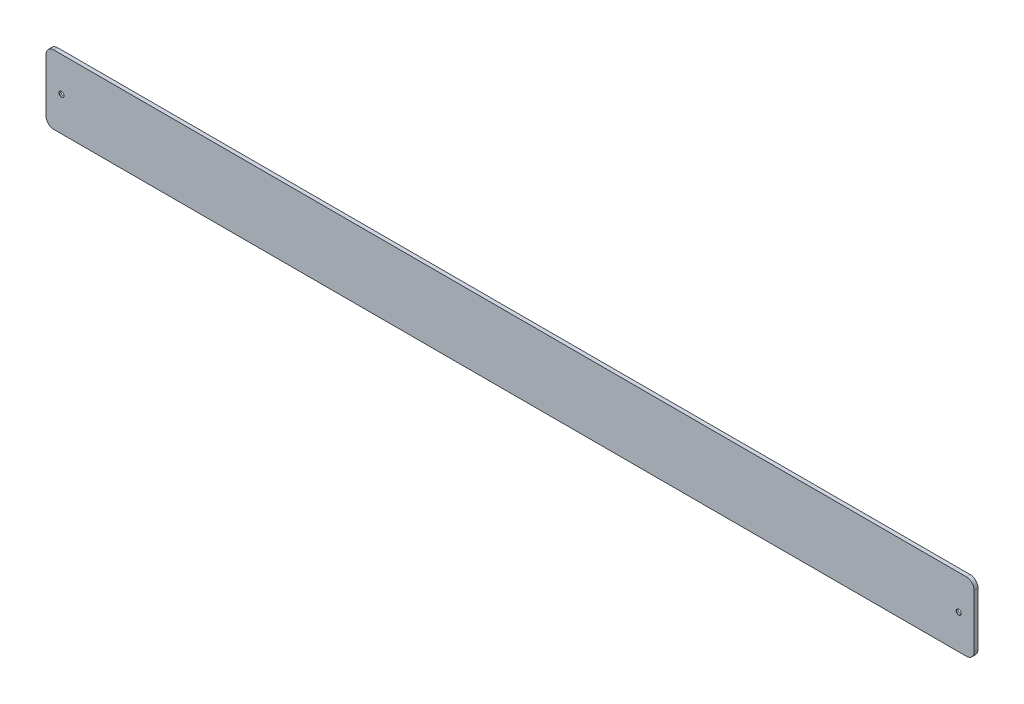
SolidWorks part; units mm, degrees
ref_plane "Plan de face" through (0, 0, 0) normal (0, 0, 1) x (1, 0, 0)
ref_plane "Plan de dessus" through (0, 0, 0) normal (0, 1, 0) x (1, 0, 0)
ref_plane "Plan de droite" through (0, 0, 0) normal (1, 0, 0) x (0, 0, -1)
sketch "Esquisse1" plane through (0, 0, 0) normal (0, 0, 1) x (1, 0, 0)
  line L1 (-1067.2805, -44.5) -> (112.7195, -44.5)
  line L2 (-1077.2805, -34.5) -> (-1077.2805, 34.5)
  line L3 (-1067.2805, 44.5) -> (112.7195, 44.5)
  line L4 (122.7195, -34.5) -> (122.7195, 34.5)
  line L5 (-1077.2805, -44.5) -> (122.7195, 44.5) construction
  line L6 (-1077.2805, 44.5) -> (122.7195, -44.5) construction
  arc A0 (-1067.2805, -44.5) -> (-1077.2805, -34.5) centre (-1067.2805, -34.5) cw
  arc A1 (-1077.2805, 34.5) -> (-1067.2805, 44.5) centre (-1067.2805, 34.5) cw
  arc A2 (112.7195, -44.5) -> (122.7195, -34.5) centre (112.7195, -34.5) ccw
  arc A3 (122.7195, 34.5) -> (112.7195, 44.5) centre (112.7195, 34.5) ccw
  point P0 (-477.2805, 0)
  dimension "D3" = 10
  dimension "D1" = 89
  dimension "D2" = 1200
extrude "Boss.-Extru.1" add sketch "Esquisse1" along normal blind 5
hole_wizard "Dégagement M61" positions "Esquisse3" profile "Esquisse2" hole size "M6" standard "JIS" end condition through all
sketch "Esquisse3" plane through (0, 0, 5) normal (0, 0, 1) x (1, 0, 0)
  point P0 (-1057.2805, -0.1767)
  point P2 (102.7195, 0)
sketch "Esquisse2" plane through (-1057.2805, -0.1767, 5) normal (1, 0, 0) x (0, -1, 0)
  line L0 (0, 0) -> (0, 5)
  line L1 (0, 5) -> (3.3, 5)
  line L2 (3.3, 5) -> (3.3, 0)
  line L5 (3.3, 0) -> (0, 0)
  line L11 (0, -6.35) -> (0, 107.95) construction
  dimension "Diamètre du perçage jusqu'au prochain" = 6.6
  dimension "Profondeur du perçage jusqu'au prochain" = 5
hole_wizard "Chambrage pour vis à tête ronde bombée M61" positions "Esquisse5" profile "Esquisse4" counterbore size "M6" standard "Ansi Metric" end condition through all
sketch "Esquisse5" plane through (0, 0, 0) normal (0, 0, -1) x (-1, 0, 0)
  point P0 (-102.7195, 0)
  point P2 (1057.2805, -0.1767)
sketch "Esquisse4" plane through (102.7195, 0, 0) normal (1, 0, 0) x (0, 1, 0)
  line L0 (0, 0) -> (0, 5)
  line L1 (0, 5) -> (3.3, 5)
  line L2 (3.3, 4.625) -> (3.3, 5)
  line L3 (3.3, 4.625) -> (3.325, 4.6)
  line L4 (3.325, 4.6) -> (6.5, 4.6)
  line L5 (6.5, 4.6) -> (6.5, 0)
  line L7 (0, 0) -> (6.5, 0)
  line L9 (-3.3, 4.625) -> (-3.325, 4.6) construction
  line L11 (0, -6.35) -> (0, 107.95) construction
  dimension "Diamètre du perçage jusqu'au prochain" = 6.6
  dimension "Profondeur du perçage jusqu'au prochain" = 5
  dimension "Diamètre du chambrage" = 13
  dimension "Profondeur du chambrage" = 4.6
  dimension "Diamètre du fraisage milieu" = 6.65
  dimension "Angle du fraisage milieu" = 90
